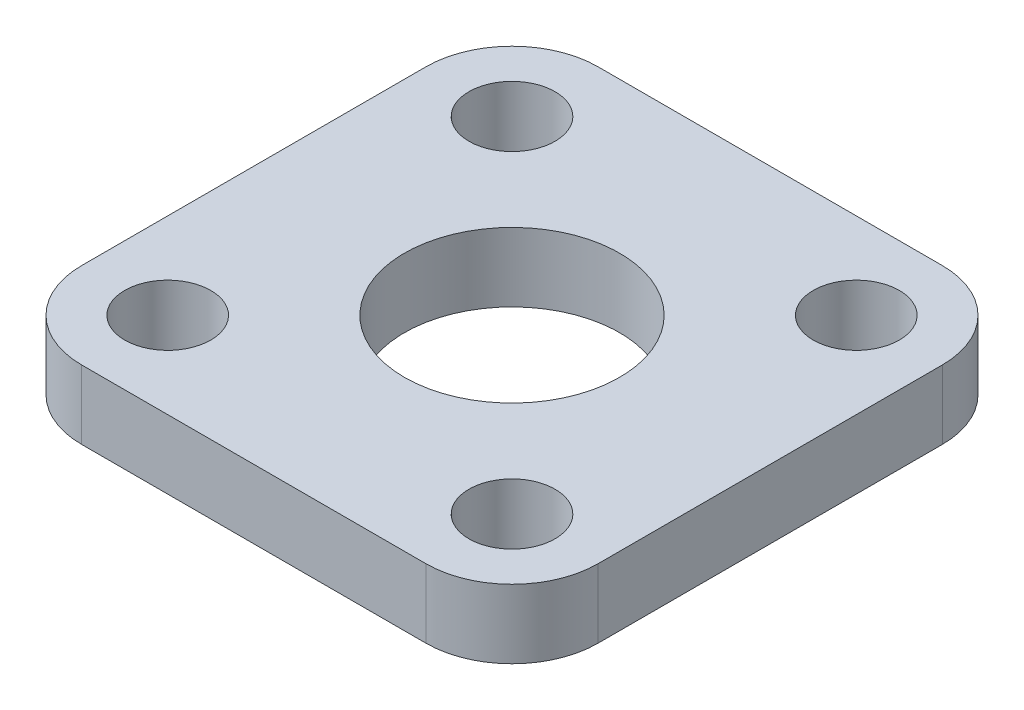
SolidWorks part; units mm, degrees
ref_plane "Front Plane" through (0, 0, 0) normal (0, 0, 1) x (1, 0, 0)
ref_plane "Top Plane" through (0, 0, 0) normal (0, 1, 0) x (1, 0, 0)
ref_plane "Right Plane" through (0, 0, 0) normal (1, 0, 0) x (0, 0, -1)
sketch "Sketch1" plane through (0, 0, 0) normal (0, 1, 0) x (1, 0, 0)
  line L1 (-6.35, -6.35) -> (6.35, -6.35) construction
  line L2 (-6.35, -6.35) -> (-6.35, 6.35) construction
  line L3 (-6.35, 6.35) -> (6.35, 6.35) construction
  line L4 (6.35, -6.35) -> (6.35, 6.35) construction
  line L5 (-6.35, -6.35) -> (6.35, 6.35) construction
  line L6 (-6.35, 6.35) -> (6.35, -6.35) construction
  line L7 (-9.525, -9.525) -> (9.525, -9.525)
  line L8 (-9.525, -9.525) -> (-9.525, 9.525)
  line L9 (-9.525, 9.525) -> (9.525, 9.525)
  line L10 (9.525, -9.525) -> (9.525, 9.525)
  line L11 (-9.525, -9.525) -> (9.525, 9.525) construction
  line L12 (-9.525, 9.525) -> (9.525, -9.525) construction
  circle A0 centre (-6.35, 6.35) radius 1.5875
  circle A1 centre (6.35, 6.35) radius 1.5875
  circle A2 centre (6.35, -6.35) radius 1.5875
  circle A3 centre (-6.35, -6.35) radius 1.5875
  circle A4 centre (0, 0) radius 3.9688
  point P0 (0, 0)
  point P6 (0, 0)
  dimension "D1" = 3.175
  dimension "D4" = 7.9375
  dimension "D2" = 19.05
  dimension "D3" = 12.7
extrude "Boss-Extrude1" add sketch "Sketch1" along normal blind 2.54
sketch "Sketch2" plane through (0, 2.54, 0) normal (0, 1, 0) x (1, 0, 0)
  circle A0 centre (0, 0) radius 4.9213
  circle A1 centre (0, 0) radius 5.715
  dimension "D1" = 9.8425
  dimension "D2" = 0.7937
extrude "Boss-Extrude2" [suppressed] add sketch "Sketch2" along normal blind 9.525
fillet "Fillet1" [suppressed] radius 0.7937
fillet "Fillet2" radius 3.175 4 edges at (9.525, 1.27, -9.525) (-9.525, 1.27, -9.525) (9.525, 1.27, 9.525) (-9.525, 1.27, 9.525)
